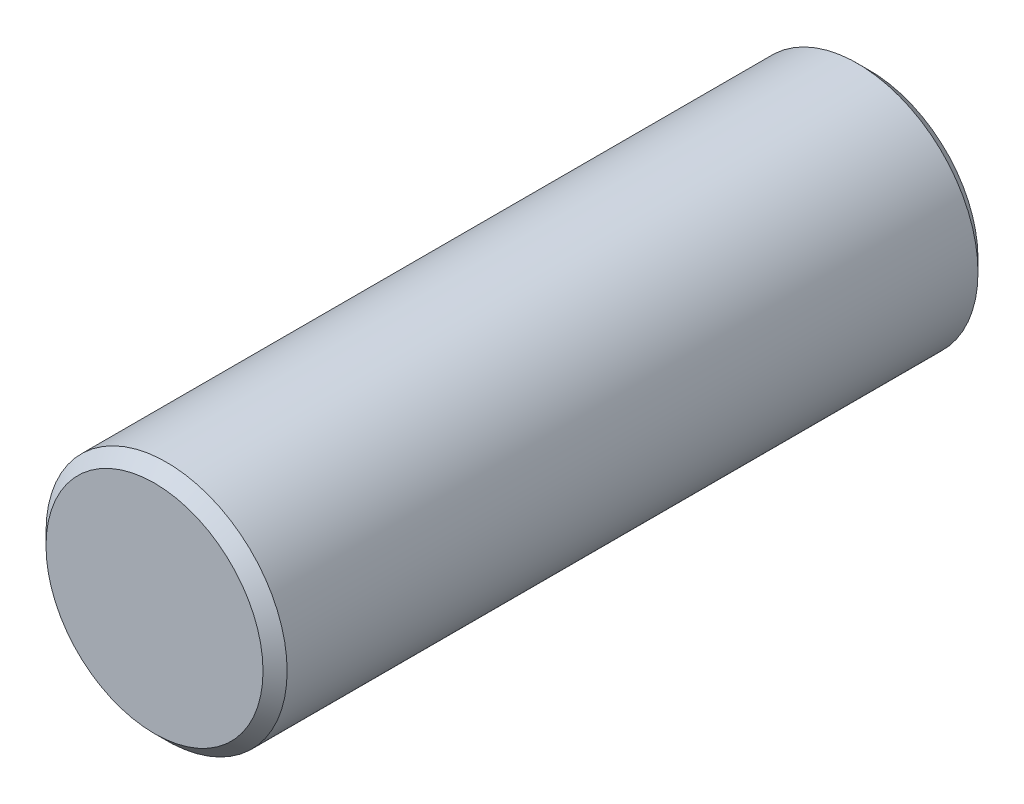
SolidWorks part; units mm, degrees
material "6061 Alloy"
ref_plane "Front Plane" through (0, 0, 0) normal (0, 0, 1) x (1, 0, 0)
ref_plane "Top Plane" through (0, 0, 0) normal (0, 1, 0) x (1, 0, 0)
ref_plane "Right Plane" through (0, 0, 0) normal (1, 0, 0) x (0, 0, -1)
sketch "Sketch3" plane through (0, 0, 0) normal (0, 0, 1) x (1, 0, 0)
  circle A0 centre (0, 0) radius 5
  dimension "D1" = 10
extrude "Boss-Extrude1" add sketch "Sketch3" along normal blind 29.65
chamfer "Chamfer1" distance 0.5 angle 45 2 edges at (5, 0, 0) (5, 0, 29.65)
